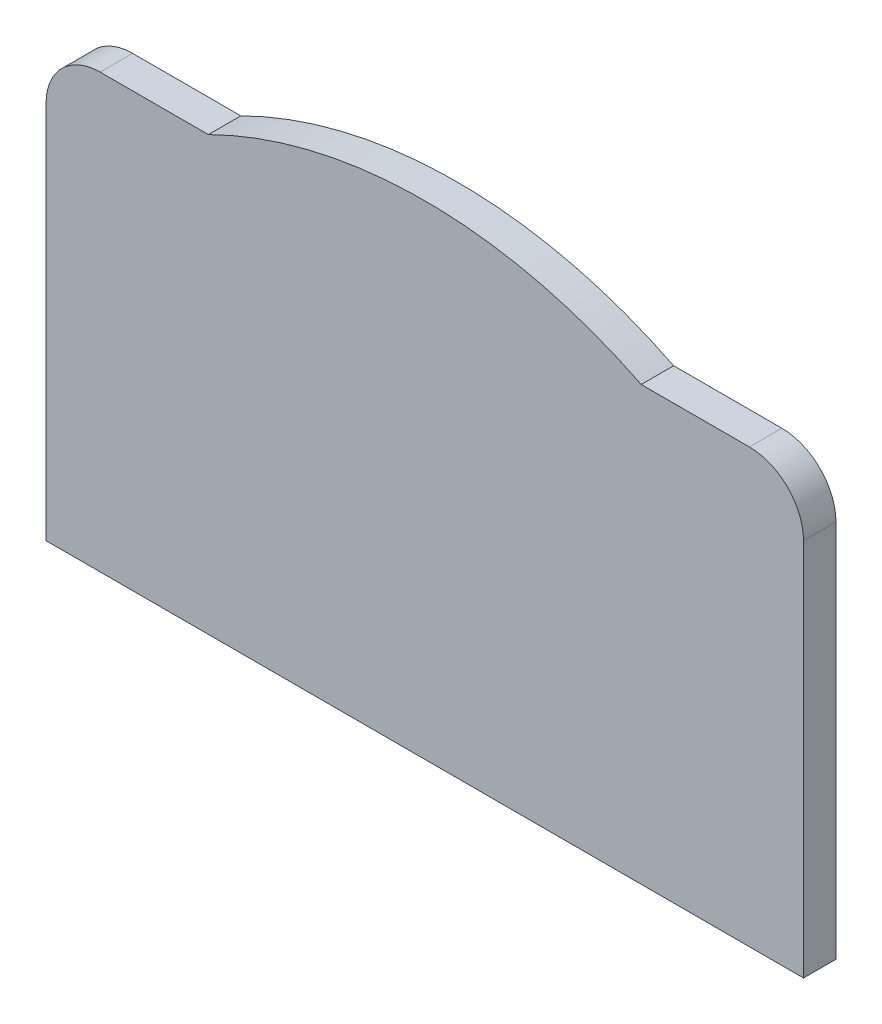
SolidWorks part; units mm, degrees
ref_plane "Plan de face" through (0, 0, 0) normal (0, 0, 1) x (1, 0, 0)
ref_plane "Plan de dessus" through (0, 0, 0) normal (0, 1, 0) x (1, 0, 0)
ref_plane "Plan de droite" through (0, 0, 0) normal (1, 0, 0) x (0, 0, -1)
sketch "Esquisse1" plane through (0, 0, 0) normal (0, 0, 1) x (1, 0, 0)
  line L1 (-60, 40) -> (80, 40)
  line L2 (-60, 40) -> (-60, -40)
  line L3 (-60, -40) -> (80, -40)
  line L4 (80, 40) -> (80, -40)
  dimension "D1" = 140
  dimension "D2" = 80
extrude "Extrusion1" add sketch "Esquisse1" along normal blind 6
fillet "Congé1" radius 10 2 edges at (-60, 40, 3) (80, 40, 3)
sketch "Esquisse6" plane through (0, 0, 0) normal (0, 0, -1) x (-1, 0, 0)
  line L0 (-70, 40) -> (50, 40) construction
  line L1 (-50, 40) -> (30, 40)
  arc A0 (30, 40) -> (-50, 40) centre (-10, -40.2367) ccw
extrude "Extrusion2" add sketch "Esquisse6" against normal up to vertex (6 mm away)
